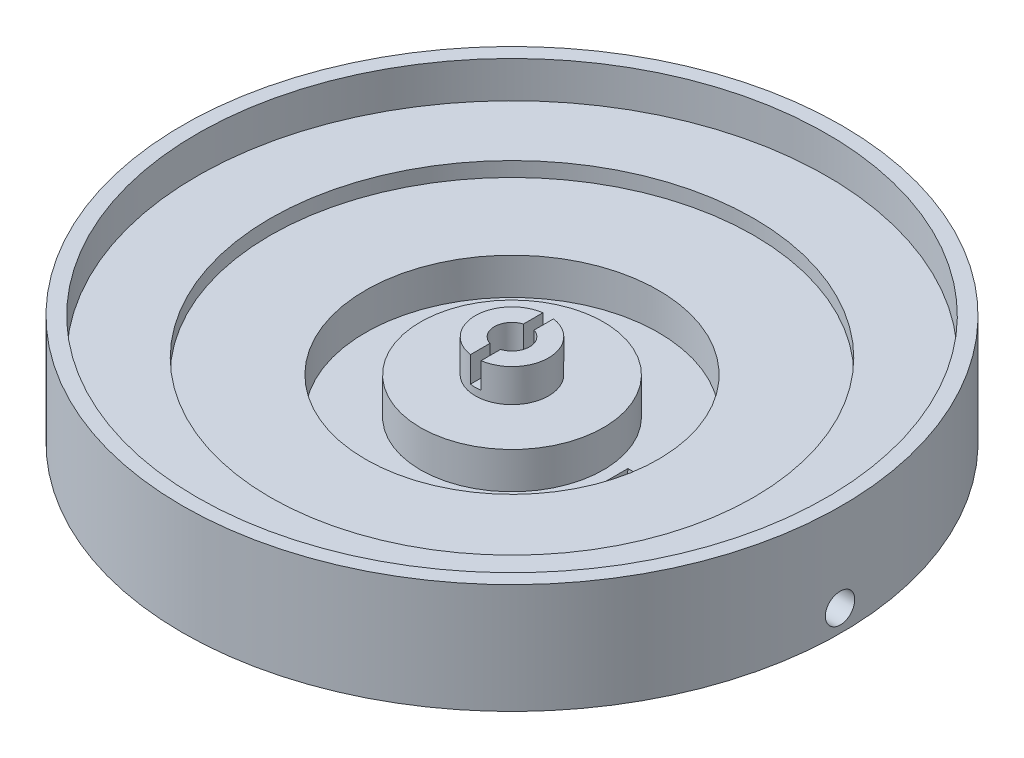
SolidWorks part; units mm, degrees
material "ABS"
ref_plane "Front Plane" through (0, 0, 0) normal (0, 0, 1) x (1, 0, 0)
ref_plane "Top Plane" through (0, 0, 0) normal (0, 1, 0) x (1, 0, 0)
ref_plane "Right Plane" through (0, 0, 0) normal (1, 0, 0) x (0, 0, -1)
sketch "Sketch1" plane through (0, 0, 0) normal (0, 1, 0) x (1, 0, 0)
  circle A0 centre (0, 0) radius 45
  dimension "D1" = 90
extrude "Boss-Extrude1" add sketch "Sketch1" along normal blind 15
shell "Shell1" thickness 2
sketch "Sketch11" plane through (0, 2, 0) normal (0, 1, 0) x (1, 0, 0)
  circle A0 centre (0, 0.5141) radius 43.5141
extrude "Boss-Extrude4" add sketch "Sketch11" along normal blind 8
sketch "Sketch12" plane through (0, 10, 0) normal (0, 1, 0) x (1, 0, 0)
  circle A0 centre (0, 0) radius 33
  dimension "D1" = 66
extrude "Cut-Extrude2" cut sketch "Sketch12" against normal blind 2
sketch "Sketch2" plane through (0, 8, 0) normal (0, 1, 0) x (1, 0, 0)
  circle A0 centre (0, 0) radius 5
  dimension "D1" = 10
extrude "Boss-Extrude2" add sketch "Sketch2" along normal blind 4.5
sketch "Sketch16" plane through (0, 12.5, 0) normal (0, 1, 0) x (1, 0, 0)
  line L1 (-0.7222, 5.5556) -> (0.7222, 5.5556)
  line L2 (-0.7222, 5.5556) -> (-0.7222, -5.5556)
  line L3 (-0.7222, -5.5556) -> (0.7222, -5.5556)
  line L4 (0.7222, 5.5556) -> (0.7222, -5.5556)
  line L5 (-0.7222, 5.5556) -> (0.7222, -5.5556) construction
  line L6 (-0.7222, -5.5556) -> (0.7222, 5.5556) construction
  point P0 (0, 0)
extrude "Cut-Extrude3" cut sketch "Sketch16" against normal blind 3.5
sketch "Sketch7" plane through (0, 12.5, 0) normal (0, 1, 0) x (1, 0, 0)
  circle A0 centre (0, 0) radius 2.4
  dimension "D1" = 4.8
extrude "Cut-Extrude1" cut sketch "Sketch7" against normal blind 3.5
sketch "Sketch18" plane through (0, 0, 0) normal (0, -1, 0) x (1, 0, 0)
  circle A0 centre (0, 0) radius 1.3
  dimension "D1" = 2.6
extrude "Cut-Extrude4" cut sketch "Sketch18" against normal blind 17
sketch "Sketch19" plane through (0, 0, 0) normal (0, -1, 0) x (1, 0, 0)
  circle A0 centre (0, 0) radius 3.5
  dimension "D1" = 7
extrude "Cut-Extrude5" cut sketch "Sketch19" against normal blind 8
ref_plane "Plane1" through (15, 0, 0) normal (1, 0, 0) x (0, 0, -1)
sketch "Sketch20" plane through (15, 0, 0) normal (1, 0, 0) x (0, 0, -1)
  circle A0 centre (-0.1694, 3) radius 2
  dimension "D1" = 4
  dimension "D2" = 3
extrude "Cut-Extrude6" cut sketch "Sketch20" along normal through all and the other way blind 1
sketch "Sketch22" plane through (0, 8, 0) normal (0, 1, 0) x (1, 0, 0)
  circle A1 centre (0, 0) radius 20
  circle A2 centre (0, 0) radius 12.5
  dimension "D1" = 40
  dimension "D2" = 25
extrude "Cut-Extrude10" cut sketch "Sketch22" against normal blind 5
sketch "Sketch23" plane through (0, 0, 0) normal (0, -1, 0) x (1, 0, 0)
  line L1 (2.8627, -5.9458) -> (6.5806, -0.4937)
  line L2 (6.5806, -0.4937) -> (3.7179, 5.4521)
  line L3 (3.7179, 5.4521) -> (-2.8627, 5.9458)
  line L4 (-2.8627, 5.9458) -> (-6.5806, 0.4937)
  line L5 (-6.5806, 0.4937) -> (-3.7179, -5.4521)
  line L6 (-3.7179, -5.4521) -> (2.8627, -5.9458)
  circle A0 centre (0, 0) radius 5.715 construction
  dimension "D1" = 11.43
extrude "Cut-Extrude11" cut sketch "Sketch23" against normal blind 6
